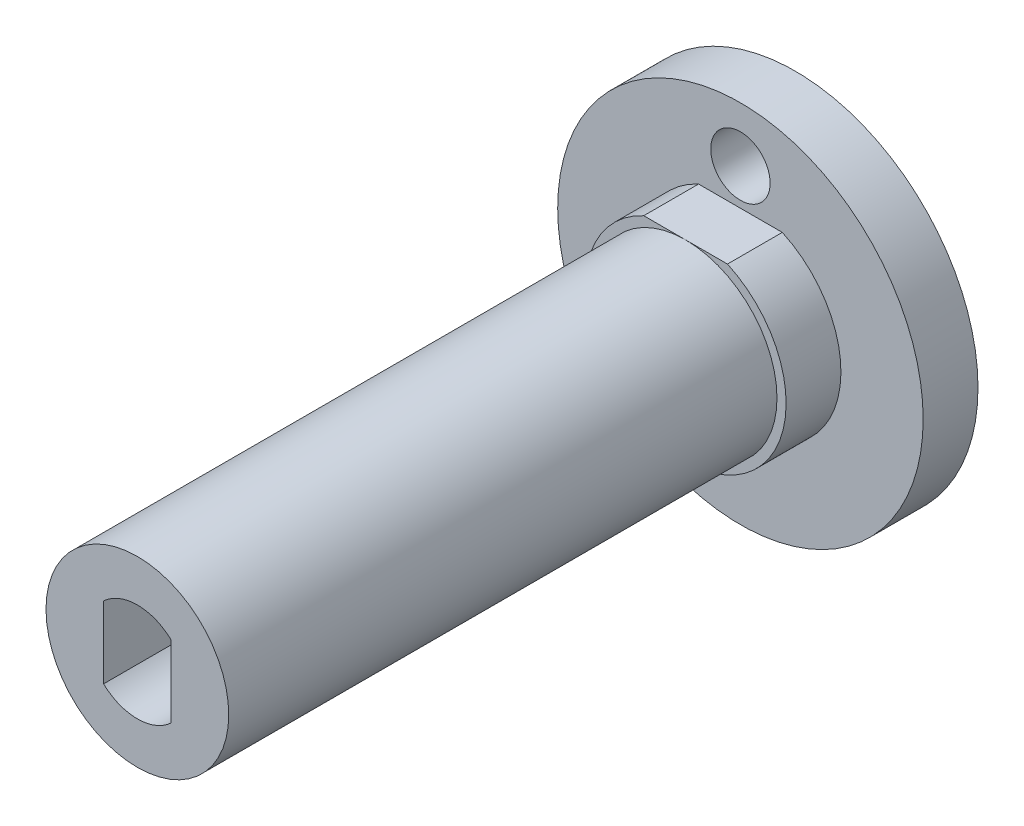
SolidWorks part; units mm, degrees
material "ABS"
ref_plane "Front Plane" through (0, 0, 0) normal (0, 0, 1) x (1, 0, 0)
ref_plane "Top Plane" through (0, 0, 0) normal (0, 1, 0) x (1, 0, 0)
ref_plane "Right Plane" through (0, 0, 0) normal (1, 0, 0) x (0, 0, -1)
sketch "Sketch1" plane through (0, 0, 0) normal (0, 0, 1) x (1, 0, 0)
  line L0 (0, 0) -> (0, 7) construction
  line L1 (0, 10) -> (26.9161, 10) construction
  circle A1 centre (0, 0) radius 10
  circle A2 centre (0, 7) radius 1.625
  dimension "D1" = 20
  dimension "D2" = 3
  dimension "D3" = 3.25
extrude "Boss-Extrude1" add sketch "Sketch1" along normal blind 3
sketch "Sketch2" plane through (0, 0, 3) normal (0, 0, 1) x (1, 0, 0)
  line L0 (-2.2913, 5) -> (2.2913, 5)
  arc A0 (-2.2913, 5) -> (2.2913, 5) centre (0, 0) ccw
  dimension "D1" = 11
  dimension "D2" = 5
extrude "Boss-Extrude2" add sketch "Sketch2" along normal blind 3
sketch "Sketch3" plane through (0, 0, 6) normal (0, 0, 1) x (1, 0, 0)
  circle A0 centre (0, 0) radius 5
  dimension "D1" = 10
extrude "Boss-Extrude3" add sketch "Sketch3" along normal blind 30
sketch "Sketch4" plane through (0, 0, 36) normal (0, 0, 1) x (1, 0, 0)
  line L2 (1.85, -1.9666) -> (1.85, 1.9666)
  line L4 (-1.85, -1.9666) -> (-1.85, 1.9666)
  line L5 (1.3174, -2.3568) -> (-1.3174, 2.3568) construction
  line L6 (1.3174, 2.3568) -> (-1.3174, -2.3568) construction
  arc A0 (1.85, 1.9666) -> (-1.85, 1.9666) centre (0, 0) ccw
  arc A1 (-1.85, -1.9666) -> (1.85, -1.9666) centre (0, 0) ccw
  dimension "D1" = 5.4
extrude "Cut-Extrude1" cut sketch "Sketch4" against normal blind 8
